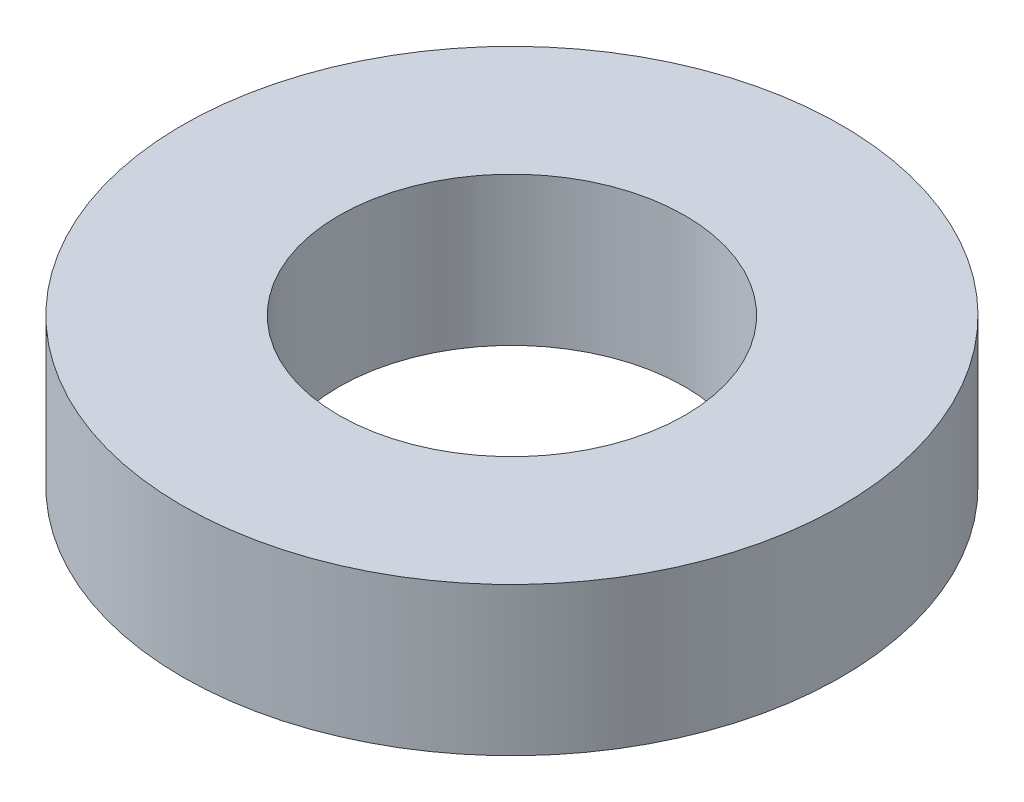
SolidWorks part; units mm, degrees
ref_plane "前视基准面" through (0, 0, 0) normal (0, 0, 1) x (1, 0, 0)
ref_plane "上视基准面" through (0, 0, 0) normal (0, 1, 0) x (1, 0, 0)
ref_plane "右视基准面" through (0, 0, 0) normal (1, 0, 0) x (0, 0, -1)
sketch "草图1" plane through (0, 0, 0) normal (0, 1, 0) x (1, 0, 0)
  circle A0 centre (0, 0) radius 2.1
  circle A1 centre (0, 0) radius 4
  dimension "D1" = 4.2
  dimension "D2" = 8
extrude "凸台-拉伸1" add sketch "草图1" along normal blind 1.8
